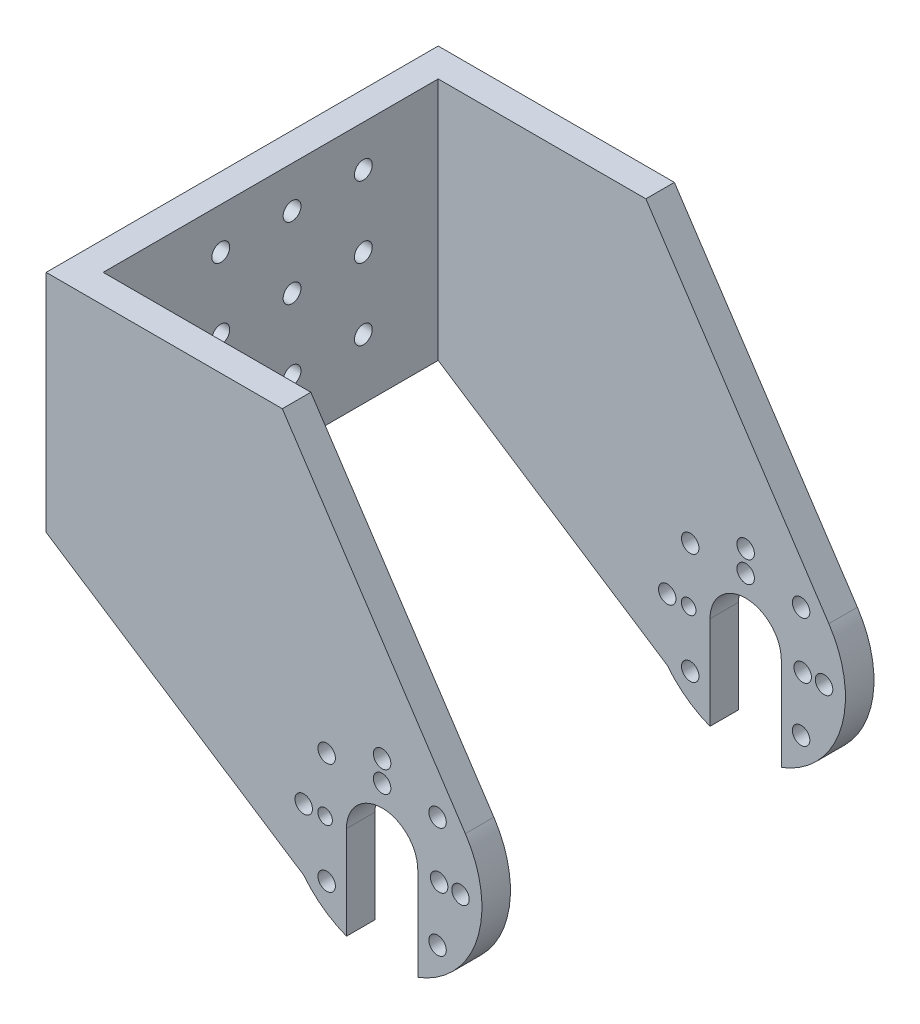
SolidWorks part; units mm, degrees
ref_plane "정면" through (0, 0, 0) normal (0, 0, 1) x (1, 0, 0)
ref_plane "윗면" through (0, 0, 0) normal (0, 1, 0) x (1, 0, 0)
ref_plane "우측면" through (0, 0, 0) normal (1, 0, 0) x (0, 0, -1)
sketch "스케치1" plane through (0, 0, 0) normal (0, 0, 1) x (1, 0, 0)
  line L0 (11.674, 7.7277) -> (-14, 46.5127)
  line L4 (-14, 46.5127) -> (-47.1329, 46.5127)
  line L5 (-11, -8.6603) -> (-47.1329, 14.9217)
  line L8 (-47.1329, 46.5127) -> (-47.1329, 14.9217)
  circle A18 centre (0, 0) radius 5
  circle A19 centre (0, 8) radius 1.225
  circle A20 centre (0, 11) radius 1.225
  arc A21 (-11, -8.6603) -> (11.674, 7.7277) centre (0, 0) ccw
  circle A22 centre (7.7782, 7.7782) radius 1.225
  circle A23 centre (8, 0) radius 1.225
  circle A24 centre (11, 0) radius 1.225
  circle A25 centre (7.7782, -7.7782) radius 1.225
  circle A26 centre (0, -8) radius 1.225
  circle A27 centre (0, -11) radius 1.225
  circle A28 centre (-7.7782, -7.7782) radius 1.225
  circle A29 centre (-8, 0) radius 1.025
  circle A30 centre (-11, 0) radius 1.225
  circle A31 centre (-7.7782, 7.7782) radius 1.225
  dimension "D1" = 10
  dimension "D3" = 2.45
  dimension "D5" = 28
  dimension "D6" = 2.05
  dimension "D2" = 8
  dimension "D4" = 11
  dimension "D7" = 7.7782
  dimension "D8" = 8
  dimension "D9" = 11
  dimension "D10" = 11.674
  dimension "D11" = 7.7782
  dimension "D12" = 8
  dimension "D13" = 14
  dimension "D14" = 47.1329
  dimension "D15" = 7.7782
  dimension "D16" = 11
  dimension "D17" = 14.9217
  dimension "D18" = 7.7782
  dimension "D19" = 8
  dimension "D20" = 11
extrude "보스-돌출1" add sketch "스케치1" along normal blind 55
sketch "스케치2" plane through (0, 46.5127, 0) normal (0, 1, 0) x (1, 0, 0)
  line L0 (-43.1329, -4) -> (14, -4)
  line L1 (14, -55) -> (14, 0) construction
  line L2 (14, -4) -> (14, -51)
  line L3 (14, -51) -> (-43.1329, -51)
  line L4 (-43.1329, -51) -> (-43.1329, -4)
  line L5 (-14, 0) -> (-47.1329, 0) construction
  line L6 (-47.1329, -55) -> (-47.1329, 0) construction
  point P4 (-30.5665, 0)
  dimension "D1" = 4
  dimension "D2" = 47
  dimension "D3" = 4
extrude "컷-돌출1" cut sketch "스케치2" against normal blind 66
sketch "스케치3" plane through (-47.1329, 0, 0) normal (-1, 0, 0) x (0, 0, 1)
  line L0 (0, 46.5127) -> (0, 14.9217) construction
  line L3 (55, 14.9217) -> (0, 14.9217) construction
  circle A0 centre (24.5, 30.7172) radius 1.25
  circle A1 centre (14.5, 40.7172) radius 1.25
  circle A2 centre (34.5, 30.7172) radius 1.25
  circle A3 centre (24.5, 40.7172) radius 1.25
  circle A4 centre (14.5, 30.7172) radius 1.25
  circle A5 centre (34.5, 40.7172) radius 1.25
  circle A6 centre (14.5, 20.7172) radius 1.25
  circle A7 centre (24.5, 20.7172) radius 1.25
  circle A8 centre (34.5, 20.7172) radius 1.25
  circle A45 centre (29.5, 30.7172) radius 1.25 [skipped]
  circle A46 centre (19.5, 30.7172) radius 1.25 [skipped]
  dimension "D1" = 2
  dimension "D5" = 2.5
  dimension "D6" = 14.5
  dimension "D7" = 19.5
  dimension "D8" = 29.5
  dimension "D9" = 5.7955
  dimension "D10" = 15.7955
  dimension "D11" = 25.7955
  dimension "D2" = 3
  dimension "D3" = 3
  dimension "D4" = 2
extrude "컷-돌출2" cut sketch "스케치3" against normal blind 49
sketch "스케치4" plane through (0, 0, 55) normal (0, 0, 1) x (1, 0, 0)
  line L0 (0, 5) -> (0, -5) construction
  line L1 (5, 0) -> (-5, 0) construction
  line L2 (-5, 0) -> (-5, -13.0767)
  line L3 (5, 0) -> (5, -13.0767)
  line L4 (-5, 0) -> (5, 0)
  circle A0 centre (0, 0) radius 5 construction
  arc A1 (-11, -8.6603) -> (11.674, 7.7277) centre (0, 0) ccw construction
  arc A2 (-5, -13.0767) -> (5, -13.0767) centre (0, 0) ccw
extrude "컷-돌출3" cut sketch "스케치4" against normal blind 56
